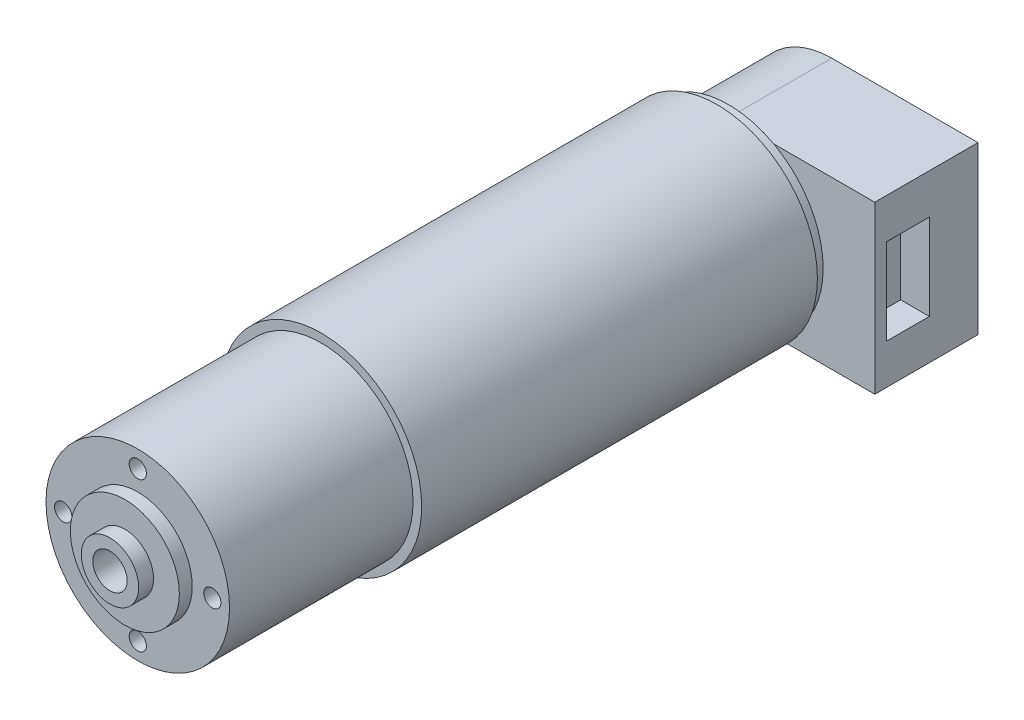
SolidWorks part; units mm, degrees
material "1060 합금"
ref_plane "정면" through (0, 0, 0) normal (0, 0, 1) x (1, 0, 0)
ref_plane "윗면" through (0, 0, 0) normal (0, 1, 0) x (1, 0, 0)
ref_plane "우측면" through (0, 0, 0) normal (1, 0, 0) x (0, 0, -1)
sketch "스케치1" plane through (0, 0, 0) normal (0, 0, 1) x (1, 0, 0)
  circle A0 centre (0, 0) radius 17.5
extrude "보스-돌출1" add sketch "스케치1" along normal blind 69
sketch "스케치2" plane through (0, 0, 69) normal (0, 0, 1) x (1, 0, 0)
  circle A0 centre (0, 0) radius 16
extrude "보스-돌출2" add sketch "스케치2" along normal blind 26
sketch "스케치3" plane through (0, 0, 95) normal (0, 0, 1) x (1, 0, 0)
  circle A0 centre (0, 0) radius 16
extrude "보스-돌출3" add sketch "스케치3" along normal blind 6
sketch "스케치4" plane through (0, 0, 101) normal (0, 0, 1) x (1, 0, 0)
  circle A0 centre (0, 0) radius 9.5
extrude "보스-돌출4" add sketch "스케치4" along normal blind 2.25
sketch "스케치5" plane through (0, 0, 103.25) normal (0, 0, 1) x (1, 0, 0)
  circle A0 centre (0, 0) radius 5
extrude "보스-돌출5" add sketch "스케치5" along normal blind 2.6
sketch "스케치6" plane through (0, 0, 105.85) normal (0, 0, 1) x (1, 0, 0)
  circle A0 centre (0, 0) radius 3
sketch "스케치8" plane through (0, 0, 0) normal (0, 0, -1) x (-1, 0, 0)
  circle A0 centre (0, 0) radius 16.5
extrude "보스-돌출7" add sketch "스케치8" along normal blind 2
sketch "스케치9" plane through (0, 0, -2) normal (0, 0, -1) x (-1, 0, 0)
  line L0 (0, 14.5) -> (-25.5, 14.5)
  line L1 (0, -14.5) -> (-25.5, -14.5)
  line L2 (-25.5, 14.5) -> (-25.5, -14.5)
  arc A0 (0, -14.5) -> (0, 14.5) centre (0, 0) ccw
extrude "보스-돌출8" add sketch "스케치9" along normal blind 18
sketch "스케치10" plane through (25.5, 0, 0) normal (1, 0, 0) x (0, 0, -1)
  line L6 (4.0109, 7.5) -> (11.5109, 7.5)
  line L7 (4.0109, 7.5) -> (4.0109, -7.5)
  line L8 (4.0109, -7.5) -> (11.5109, -7.5)
  line L9 (11.5109, 7.5) -> (11.5109, -7.5)
extrude "컷-돌출2" cut sketch "스케치10" against normal blind 5
sketch "스케치7" plane through (0, 0, 101) normal (0, 0, 1) x (1, 0, 0)
  circle A1 centre (0, 13) radius 1.5
extrude "컷-돌출1" cut sketch "스케치7" against normal blind 3.8
pattern_circular "원형 패턴1" count 4 over 360 about axis through (0, 0, 0) along (0, 0, 1) of "컷-돌출1"
extrude "컷-돌출3" cut sketch "스케치6" against normal blind 10
